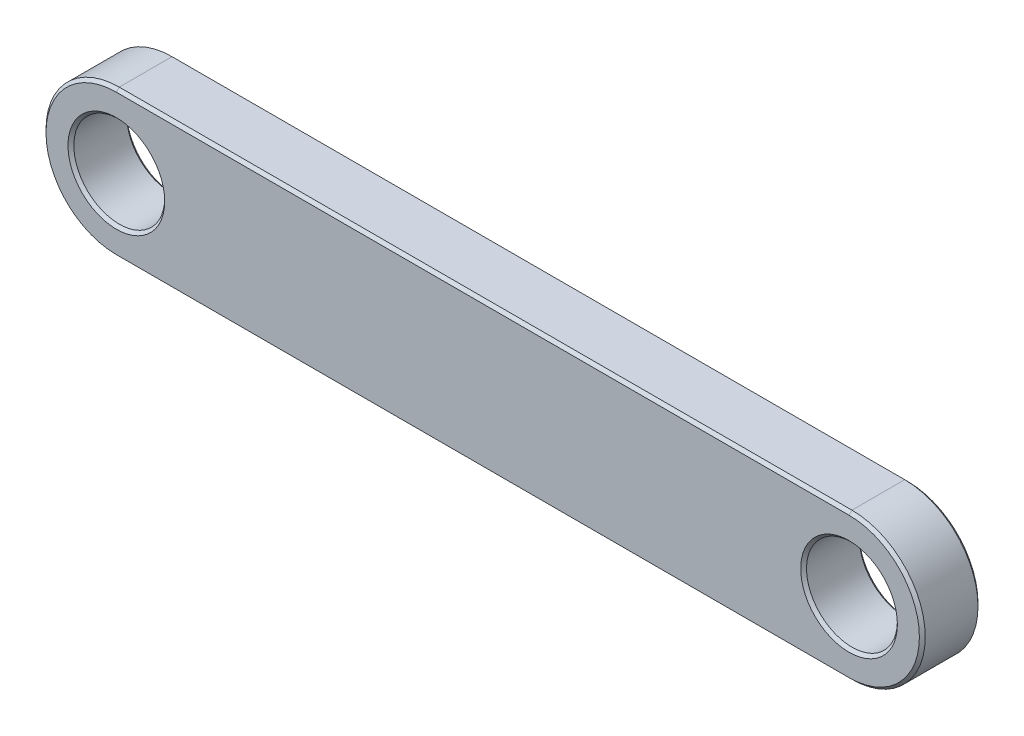
SolidWorks part; units mm, degrees
ref_plane "Front Plane" through (0, 0, 0) normal (0, 0, 1) x (1, 0, 0)
ref_plane "Top Plane" through (0, 0, 0) normal (0, 1, 0) x (1, 0, 0)
ref_plane "Right Plane" through (0, 0, 0) normal (1, 0, 0) x (0, 0, -1)
sketch "Sketch1" plane through (0, 0, 0) normal (0, 0, 1) x (1, 0, 0)
  line L0 (-12.5, 0) -> (12.5, 0) construction
  line L1 (-12.5, 2.5) -> (12.5, 2.5)
  line L2 (-12.5, -2.5) -> (12.5, -2.5)
  arc A0 (-12.5, 2.5) -> (-12.5, -2.5) centre (-12.5, 0) ccw
  arc A1 (12.5, -2.5) -> (12.5, 2.5) centre (12.5, 0) ccw
  circle A2 centre (-12.5, 0) radius 1.55
  circle A3 centre (12.5, 0) radius 1.55
  point P2 (0, 0)
  dimension "D2" = 2.5
  dimension "D3" = 3.1
  dimension "D4" = 3.1
  dimension "D1" = 25
extrude "Boss-Extrude1" add sketch "Sketch1" along normal blind 2
chamfer "Chamfer1" distance 0.1 angle 45 12 edges at (14.05, 0, 0) (-10.95, 0, 0) (0, -2.5, 0) (15, 0, 0) (0, 2.5, 0) (-15, 0, 0) (14.05, 0, 2) (0, 2.5, 2) (15, 0, 2) (0, -2.5, 2) (-15, 0, 2) (-10.95, 0, 2)
